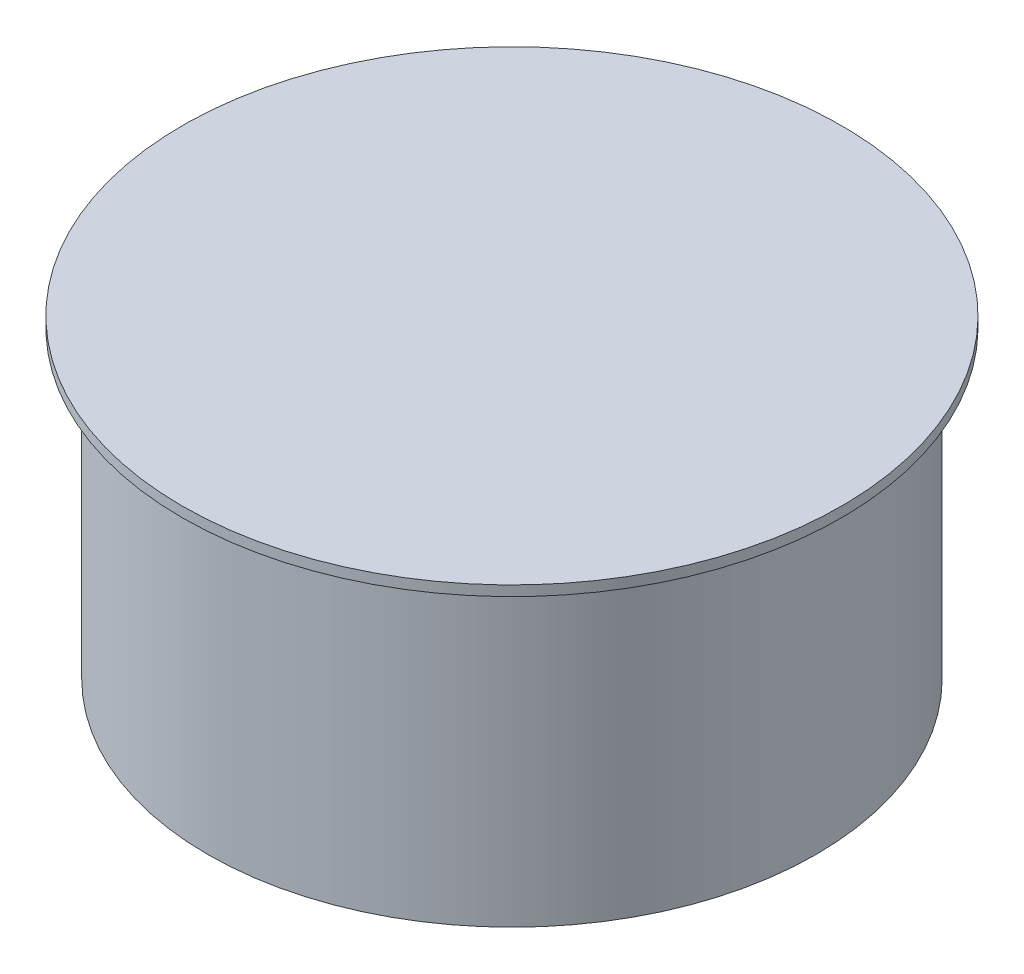
SolidWorks part; units mm, degrees
ref_plane "Front Plane" through (0, 0, 0) normal (0, 0, 1) x (1, 0, 0)
ref_plane "Top Plane" through (0, 0, 0) normal (0, 1, 0) x (1, 0, 0)
ref_plane "Right Plane" through (0, 0, 0) normal (1, 0, 0) x (0, 0, -1)
sketch "Sketch1" plane through (0, 0, 0) normal (0, 1, 0) x (1, 0, 0)
  circle A0 centre (0, 0) radius 152.4
extrude "Boss-Extrude1" add sketch "Sketch1" along normal blind 152.4
sketch "Sketch3" plane through (0, 152.4, 0) normal (0, 1, 0) x (1, 0, 0)
  circle A0 centre (0, 0) radius 165.1
  point P0 (0, 0)
extrude "Boss-Extrude2" add sketch "Sketch3" along normal blind 5.08
